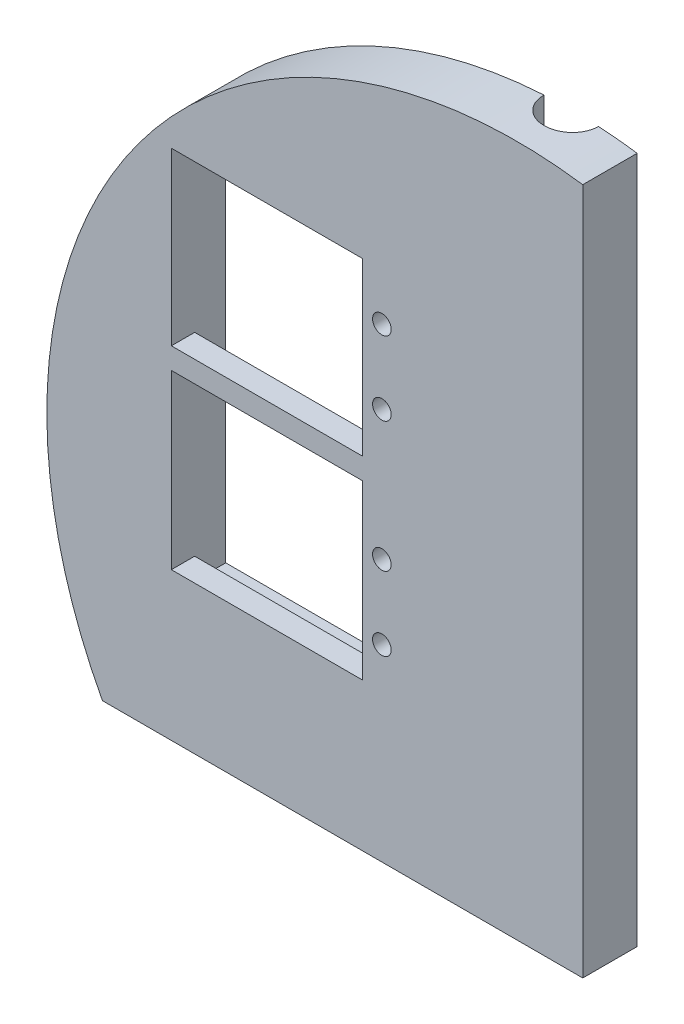
SolidWorks part; units mm, degrees
ref_plane "Front Plane" through (0, 0, 0) normal (1, 0, 0) x (0, 1, 0)
ref_plane "Top Plane" through (0, 0, 0) normal (0, 0, 1) x (0, 1, 0)
ref_plane "Right Plane" through (0, 0, 0) normal (0, 1, 0) x (-1, 0, 0)
sketch "Sketch1" plane through (0, 0, 0) normal (0, 0, 1) x (0, 1, 0)
  circle A0 centre (0, 0) radius 60.5
  dimension "D1" = 121
extrude "Boss-Extrude1" add sketch "Sketch1" along normal blind 7
sketch "Sketch6" plane through (0, 60.5, -6) normal (0, 1, 0) x (-1, 0, 0)
  circle A0 centre (0, 6) radius 3.5
  dimension "D1" = 7
extrude "Cut-Extrude2" cut sketch "Sketch6" against normal blind 70
sketch "Sketch13" plane through (0, 0, 7) normal (0, 0, 1) x (1, 0, 0)
  line L0 (-28, 43.5) -> (-5, 43.5)
  line L2 (-5, 20.5) -> (-28, 20.5)
  line L3 (-28, 20.5) -> (-28, 43.5)
  line L4 (-5, 43.5) -> (-5, 20.5)
sketch "Sketch21" plane through (0, 0, 7) normal (0, 0, 1) x (1, 0, 0)
  line L0 (8.4878, 59.9016) -> (8.4878, -28.5421)
  line L1 (8.4878, 59.9016) -> (8.4878, -28.5421) construction
  line L2 (8.4878, -28.5421) -> (-53.3441, -28.5421)
  circle A0 centre (0, 0) radius 60.5 construction
  arc A1 (-3.5, 60.3987) -> (3.5, 60.3987) centre (0, 0) ccw construction
  arc A2 (-53.3441, -28.5421) -> (8.4878, 59.9016) centre (38.0661, -26.6124) ccw
  dimension "D1" = 91.4306
  dimension "D2" = 28.5421
extrude "Cut-Extrude7" cut sketch "Sketch21" against normal blind 10
sketch "Sketch23" plane through (0, 0, 0) normal (0, 0, -1) x (1, 0, 0)
  line L0 (-44.4724, 12.2383) -> (-2, 12.2383)
  line L1 (-2, 12.2383) -> (-2, -37.4903)
  line L2 (-2, -37.4903) -> (-44.4724, -37.4903)
  line L3 (-44.4724, -37.4903) -> (-44.4724, 12.2383)
extrude "Cut-Extrude8" cut sketch "Sketch23" against normal blind 4
ref_plane "Plane1" through (-2, 0, 0) normal (-1, 0, 0) x (0, -1, 0)
sketch "Sketch24" plane through (-2, 0, 0) normal (-1, 0, 0) x (0, -1, 0)
  line L2 (-37.4903, 2.8723) -> (-37.4903, 4)
  line L3 (-37.4903, 4) -> (12.2383, 4)
  line L4 (12.2383, 4) -> (12.2383, 2.8723)
  line L5 (12.2383, 4) -> (12.2383, 0) construction
  line L6 (12.2383, 2.8723) -> (-37.4903, 2.8723)
  point P4 (12.2383, 4)
extrude "Cut-Extrude10" cut sketch "Sketch24" against normal blind 1
ref_plane "Plane3" through (-5.4724, 0, 0) normal (1, 0, 0) x (0, 1, 0)
hole_wizard "CSK for M2 Flat Head Machine Screw1" positions "Sketch33" profile "Sketch32" countersink size "M2" standard "ANSI Metric" end condition through all
sketch "Sketch33" plane through (0, 0, 4) normal (0, 0, -1) x (0, 1, 0)
  point P0 (-4.3075, -17.3736)
  point P3 (5.1925, -17.3777)
  point P6 (21.9269, -17.3715)
  point P9 (31.4269, -17.3715)
sketch "Sketch32" plane through (-17.3736, -4.3075, 4) normal (1, 0, 0) x (0, 1, 0)
  line L0 (0, 0) -> (0, 3)
  line L1 (0, 3) -> (1.2, 3)
  line L2 (1.2, 3) -> (1.2, 1)
  line L3 (1.2, 1) -> (2.2, 0)
  line L5 (2.2, 0) -> (0, 0)
  line L6 (-1.2, 1) -> (-2.2, 0) construction
  line L11 (0, -6.35) -> (0, 107.95) construction
  dimension "Thru Hole Dia." = 2.4
  dimension "Thru Hole Depth" = 3
  dimension "Near C'Sink Dia." = 4.4
  dimension "Near C'Sink Angle" = 90
sketch "Sketch30" plane through (0, 0, 4) normal (0, 0, -1) x (1, 0, 0)
  line L0 (-44.4724, -15.4564) -> (-19.8821, -15.4564)
  line L1 (-44.4724, 12.2383) -> (-44.4724, -37.4903) construction
  line L2 (-19.8821, -15.4564) -> (-19.8821, -37.4903)
  line L3 (-44.4724, -37.4903) -> (-3.5, -37.4903) construction
  line L4 (-19.8821, -37.4903) -> (-44.4724, -37.4903)
  line L5 (-44.4724, -37.4903) -> (-44.4724, -15.4564)
  line L6 (-19.8821, -12.7137) -> (-44.4724, -12.7137)
  line L7 (-44.4724, -12.7137) -> (-44.4724, 9.5008)
  line L8 (-44.4724, 9.5008) -> (-19.8715, 9.5008)
  line L9 (-19.8715, 9.5008) -> (-19.8821, -12.7137)
  point P14 (-38.4095, -12.4903)
  point P15 (-19.8821, -12.7137)
extrude "Cut-Extrude11" cut sketch "Sketch30" against normal blind 10
sketch "Sketch39" plane through (0, -9.5, 0) normal (0, 1, 0) x (-1, 0, 0)
  circle A0 centre (0, 0) radius 2.5
  dimension "D1" = 5
ref_plane "Plane4" through (3.4878, 0, 0) normal (1, 0, 0) x (0, 1, 0)
extrude "Cut-Extrude14" cut sketch "Sketch39" against normal blind 13
ref_plane "Plane5" through (0, -15.7383, 0) normal (0, 1, 0) x (-1, 0, 0)
sketch "Sketch42" plane through (0, -15.7383, 0) normal (0, 1, 0) x (-1, 0, 0)
  arc A0 (0.2014, 1.0166) -> (-0.2014, -1.0166) centre (0, 0) ccw construction
  arc A1 (-0.2014, -1.0166) -> (0.2014, 1.0166) centre (0, 0) ccw construction
  arc A2 (0.2014, 1.0166) -> (-0.2014, -1.0166) centre (0, 0) ccw construction
  arc A3 (-0.2014, -1.0166) -> (0.2014, 1.0166) centre (0, 0) ccw construction
  circle A4 centre (0, 0) radius 3.1
  dimension "D1" = 6.2
extrude "Cut-Extrude15" cut sketch "Sketch42" against normal mid plane 2
ref_plane "Plane6" through (-2, 0, 0) normal (-1, 0, 0) x (0, -1, 0)
sketch "Sketch43" plane through (-2, 0, 0) normal (-1, 0, 0) x (0, -1, 0)
  line L0 (12.2383, 1.5) -> (12.2383, 2.8723)
  line L1 (12.2383, 2.8723) -> (9.5, 2.8723)
  line L2 (9.5, 2.8723) -> (9.5, 1.5)
  line L3 (9.5, 1.5) -> (12.2383, 1.5)
extrude "Cut-Extrude17" cut sketch "Sketch43" against normal blind 1
ref_plane "Plane7" through (-1, 0, 0) normal (-1, 0, 0) x (0, -1, 0)
sketch "Sketch44" plane through (-1, 0, 0) normal (-1, 0, 0) x (0, -1, 0)
  line L0 (12.2383, 2.2913) -> (12.2383, 3.3537)
  line L1 (12.2383, 3.3537) -> (9.5, 3.3537)
  line L3 (9.5, 3.3537) -> (9.5, 2.2913)
  line L4 (9.5, 2.2913) -> (12.2383, 2.2913)
  line L6 (9.5, 2.2913) -> (12.2383, 2.2913) construction
